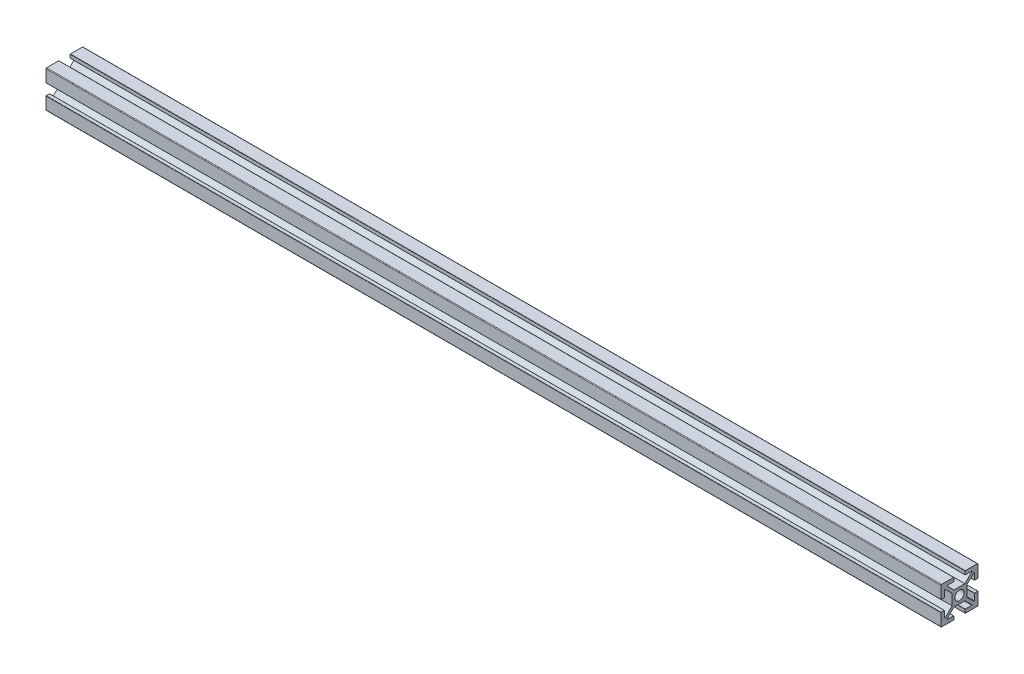
SolidWorks part; units mm, degrees
ref_plane "Front Plane" through (0, 0, 0) normal (0, 0, 1) x (1, 0, 0)
ref_plane "Top Plane" through (0, 0, 0) normal (0, 1, 0) x (1, 0, 0)
ref_plane "Right Plane" through (0, 0, 0) normal (1, 0, 0) x (0, 0, -1)
sketch "Sketch1" plane through (0, 0, 0) normal (1, 0, 0) x (0, 0, -1)
  line L0 (-7.4274, 2.1557) -> (-5.7274, 2.1557)
  line L1 (-0.7274, 9.1557) -> (-7.2274, 9.1557)
  line L2 (-7.5774, 2.3057) -> (-7.5774, 8.8057)
  line L3 (5.4021, 3.1557) -> (-0.4643, 3.1557)
  line L4 (-1.5311, -3.7897) -> (-1.5311, 2.1011)
  line L5 (-5.5774, 2.3057) -> (-5.5774, 5.7419)
  line L6 (-4.1455, 7.1557) -> (-0.7274, 7.1557)
  line L7 (-0.5774, 7.3057) -> (-0.5774, 9.0057)
  line L8 (-5.5774, 7.1557) -> (-1.5311, 3.1557) construction
  line L9 (-5.3219, 5.8486) -> (-1.5311, 2.1011)
  line L10 (-4.2509, 6.899) -> (-0.4643, 3.1557)
  line L11 (10.5152, 7.1557) -> (6.4689, 3.1557) construction
  line L12 (2.4689, -0.8443) -> (2.4689, 10.8443) construction
  line L13 (2.4689, -0.8443) -> (-12.5152, -0.8443) construction
  line L14 (9.1887, 6.899) -> (5.4021, 3.1557)
  line L15 (10.2598, 5.8486) -> (6.4689, 2.1011)
  line L16 (5.5152, 7.3057) -> (5.5152, 9.0057)
  line L17 (9.0833, 7.1557) -> (5.6652, 7.1557)
  line L18 (10.5152, 2.3057) -> (10.5152, 5.7419)
  line L19 (6.4689, -3.7897) -> (6.4689, 2.1011)
  line L20 (12.5152, 2.3057) -> (12.5152, 8.8057)
  line L21 (5.6652, 9.1557) -> (12.1652, 9.1557)
  line L22 (12.3652, 2.1557) -> (10.6652, 2.1557)
  line L23 (10.5152, -8.8443) -> (6.4689, -4.8443) construction
  line L24 (-5.5774, -8.8443) -> (-1.5311, -4.8443) construction
  line L25 (12.3652, -3.8443) -> (10.6652, -3.8443)
  line L26 (5.6652, -10.8443) -> (12.1652, -10.8443)
  line L27 (12.5152, -3.9943) -> (12.5152, -10.4943)
  line L28 (10.5152, -3.9943) -> (10.5152, -7.4305)
  line L29 (9.0833, -8.8443) -> (5.6652, -8.8443)
  line L30 (5.5152, -8.9943) -> (5.5152, -10.6943)
  line L31 (10.2598, -7.5372) -> (6.4689, -3.7897)
  line L32 (9.1887, -8.5876) -> (5.4021, -4.8443)
  line L33 (-4.2509, -8.5876) -> (-0.4643, -4.8443)
  line L34 (-5.3219, -7.5372) -> (-1.5311, -3.7897)
  line L35 (-0.5774, -8.9943) -> (-0.5774, -10.6943)
  line L36 (-4.1455, -8.8443) -> (-0.7274, -8.8443)
  line L37 (-5.5774, -3.9943) -> (-5.5774, -7.4305)
  line L38 (5.4021, -4.8443) -> (-0.4643, -4.8443)
  line L39 (-7.5774, -3.9943) -> (-7.5774, -10.4943)
  line L40 (-0.7274, -10.8443) -> (-7.2274, -10.8443)
  line L41 (-7.4274, -3.8443) -> (-5.7274, -3.8443)
  circle A0 centre (2.4689, -0.8443) radius 2.5
  arc A1 (-7.5774, 8.8057) -> (-7.2274, 9.1557) centre (-7.2274, 8.8057) cw
  arc A2 (-7.4274, 2.1557) -> (-7.5774, 2.3057) centre (-7.4274, 2.3057) cw
  arc A3 (-5.7274, 2.1557) -> (-5.5774, 2.3057) centre (-5.7274, 2.3057) ccw
  arc A4 (-0.7274, 9.1557) -> (-0.5774, 9.0057) centre (-0.7274, 9.0057) cw
  arc A5 (-0.7274, 7.1557) -> (-0.5774, 7.3057) centre (-0.7274, 7.3057) ccw
  arc A6 (-4.2509, 6.899) -> (-4.1455, 7.1557) centre (-4.1455, 7.0057) cw
  arc A7 (-5.3219, 5.8486) -> (-5.5774, 5.7419) centre (-5.4274, 5.7419) ccw
  arc A8 (10.2598, 5.8486) -> (10.5152, 5.7419) centre (10.3652, 5.7419) cw
  arc A9 (9.1887, 6.899) -> (9.0833, 7.1557) centre (9.0833, 7.0057) ccw
  arc A10 (5.6652, 7.1557) -> (5.5152, 7.3057) centre (5.6652, 7.3057) cw
  arc A11 (5.6652, 9.1557) -> (5.5152, 9.0057) centre (5.6652, 9.0057) ccw
  arc A12 (10.6652, 2.1557) -> (10.5152, 2.3057) centre (10.6652, 2.3057) cw
  arc A13 (12.3652, 2.1557) -> (12.5152, 2.3057) centre (12.3652, 2.3057) ccw
  arc A14 (12.5152, 8.8057) -> (12.1652, 9.1557) centre (12.1652, 8.8057) ccw
  arc A15 (12.5152, -10.4943) -> (12.1652, -10.8443) centre (12.1652, -10.4943) cw
  arc A16 (12.3652, -3.8443) -> (12.5152, -3.9943) centre (12.3652, -3.9943) cw
  arc A17 (10.6652, -3.8443) -> (10.5152, -3.9943) centre (10.6652, -3.9943) ccw
  arc A18 (5.6652, -10.8443) -> (5.5152, -10.6943) centre (5.6652, -10.6943) cw
  arc A19 (5.6652, -8.8443) -> (5.5152, -8.9943) centre (5.6652, -8.9943) ccw
  arc A20 (9.1887, -8.5876) -> (9.0833, -8.8443) centre (9.0833, -8.6943) cw
  arc A21 (10.2598, -7.5372) -> (10.5152, -7.4305) centre (10.3652, -7.4305) ccw
  arc A22 (-5.3219, -7.5372) -> (-5.5774, -7.4305) centre (-5.4274, -7.4305) cw
  arc A23 (-4.2509, -8.5876) -> (-4.1455, -8.8443) centre (-4.1455, -8.6943) ccw
  arc A24 (-0.7274, -8.8443) -> (-0.5774, -8.9943) centre (-0.7274, -8.9943) cw
  arc A25 (-0.7274, -10.8443) -> (-0.5774, -10.6943) centre (-0.7274, -10.6943) ccw
  arc A26 (-5.7274, -3.8443) -> (-5.5774, -3.9943) centre (-5.7274, -3.9943) cw
  arc A27 (-7.4274, -3.8443) -> (-7.5774, -3.9943) centre (-7.4274, -3.9943) ccw
  arc A28 (-7.5774, -10.4943) -> (-7.2274, -10.8443) centre (-7.2274, -10.4943) ccw
  point P27 (5.5152, 7.1557)
  point P28 (12.5152, -10.8443)
  point P47 (6.4689, -0.8443)
  point P57 (2.4689, 3.1557)
  point P59 (5.5152, 9.1557)
  point P60 (10.5152, 2.1557)
  point P61 (12.5152, 2.1557)
  point P62 (12.5152, 9.1557)
  point P112 (-1.5311, -0.8443)
  point P113 (12.5152, -3.8443)
  point P114 (10.5152, -3.8443)
  point P115 (5.5152, -10.8443)
  point P116 (2.4689, -4.8443)
  point P117 (-0.5774, -8.8443)
  point P118 (-0.5774, -10.8443)
  point P119 (-5.5774, -3.8443)
  point P120 (5.5152, -8.8443)
  point P121 (-7.5774, -3.8443)
  point P122 (-7.5774, -10.8443)
extrude "Boss-Extrude1" add sketch "Sketch1" along normal blind 485
sketch "Sketch2" plane through (0, 3.1557, 0) normal (0, 1, 0) x (1, 0, 0)
  line L0 (0, 2.4689) -> (485, 2.4689) construction
  line L1 (0, 5.4021) -> (0, -0.4643) construction
  line L2 (485, 5.4021) -> (485, -0.4643) construction
  line L4 (0, 12.1652) -> (0, 5.6652) construction
  line L5 (485, 12.1652) -> (485, 5.6652) construction
  circle A0 centre (20, 2.4689) radius 2.5
  circle A1 centre (185, 2.4689) radius 2.5
  circle A3 centre (465, 2.4689) radius 2.5
  circle A4 centre (62, 2.4689) radius 2.5
  circle A5 centre (423, 2.4689) radius 2.5
  circle A6 centre (335, 2.4689) radius 2.5
  circle A7 centre (385, 2.4689) radius 2.5
  circle A8 centre (100, 2.4689) radius 2.5
  point P10 (242.5, 2.4689)
  dimension "D1" = 20
  dimension "D2" = 185
  dimension "D3" = 20
  dimension "D4" = 5
  dimension "D5" = 5
  dimension "D6" = 5
  dimension "D7" = 150
  dimension "D8" = 5
  dimension "D9" = 42
  dimension "D10" = 5
  dimension "D11" = 5
  dimension "D12" = 42
  dimension "D13" = 5
  dimension "D14" = 100
  dimension "D15" = 5
  dimension "D16" = 100
extrude "Cut-Extrude1" cut sketch "Sketch2" against normal blind 2
